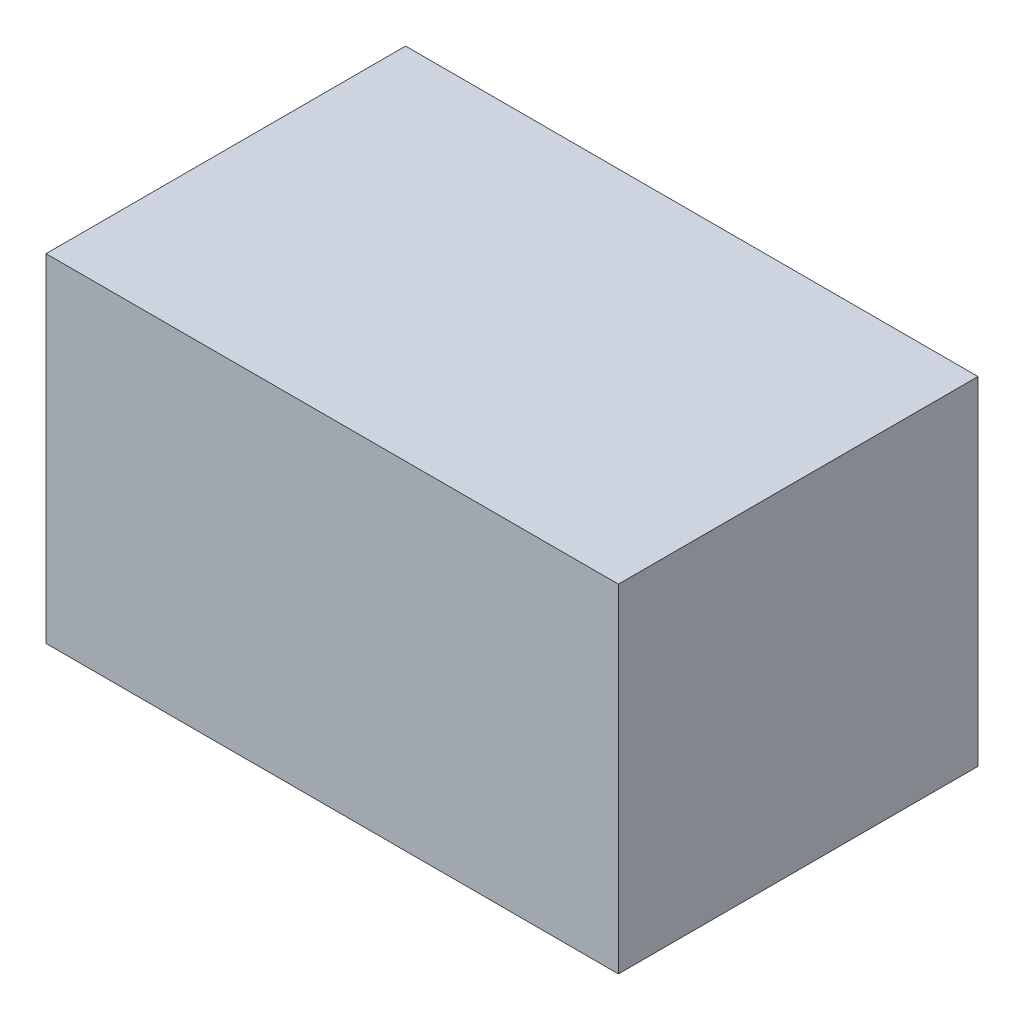
SolidWorks part; units mm, degrees
ref_plane "Front Plane" through (0, 0, 0) normal (0, 0, 1) x (1, 0, 0)
ref_plane "Top Plane" through (0, 0, 0) normal (0, 1, 0) x (1, 0, 0)
ref_plane "Right Plane" through (0, 0, 0) normal (1, 0, 0) x (0, 0, -1)
sketch "Sketch1" plane through (0, 0, 0) normal (0, 0, 1) x (1, 0, 0)
  line L1 (-39, 23) -> (39, 23)
  line L2 (-39, 23) -> (-39, -23)
  line L3 (-39, -23) -> (39, -23)
  line L4 (39, 23) -> (39, -23)
  line L5 (-39, 23) -> (39, -23) construction
  line L6 (-39, -23) -> (39, 23) construction
  point P0 (0, 0)
extrude "Boss-Extrude1" add sketch "Sketch1" along normal blind 49
